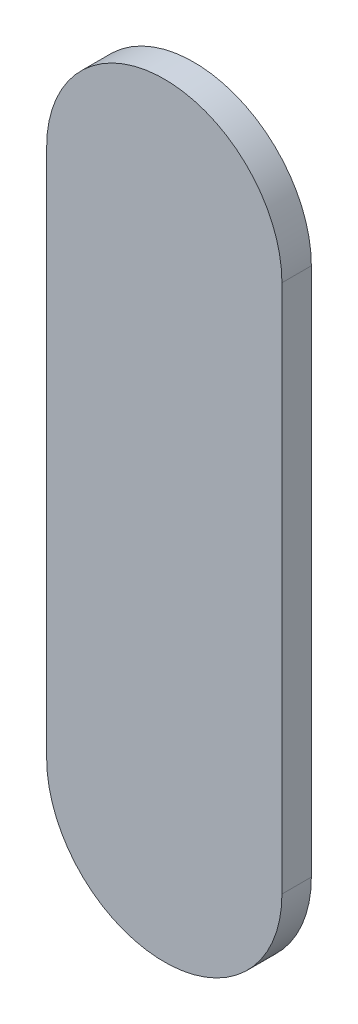
SolidWorks part; units mm, degrees
ref_plane "前视基准面" through (0, 0, 0) normal (0, 0, 1) x (1, 0, 0)
ref_plane "上视基准面" through (0, 0, 0) normal (0, 1, 0) x (1, 0, 0)
ref_plane "右视基准面" through (0, 0, 0) normal (1, 0, 0) x (0, 0, -1)
other "Configuration Table"
sketch "草图1" plane through (0, 0, 0) normal (0, 0, 1) x (1, 0, 0)
  line L0 (0, 0) -> (0, -180)
  line L1 (-40, 0) -> (-40, -180)
  line L2 (40, 0) -> (40, -180)
  circle A0 centre (0, 0) radius 40
  circle A1 centre (0, -180) radius 40
  dimension "D1" = 80
  dimension "D3" = 80
  dimension "D2" = 180
extrude "凸台-拉伸1" add sketch "草图1" along normal blind 10
